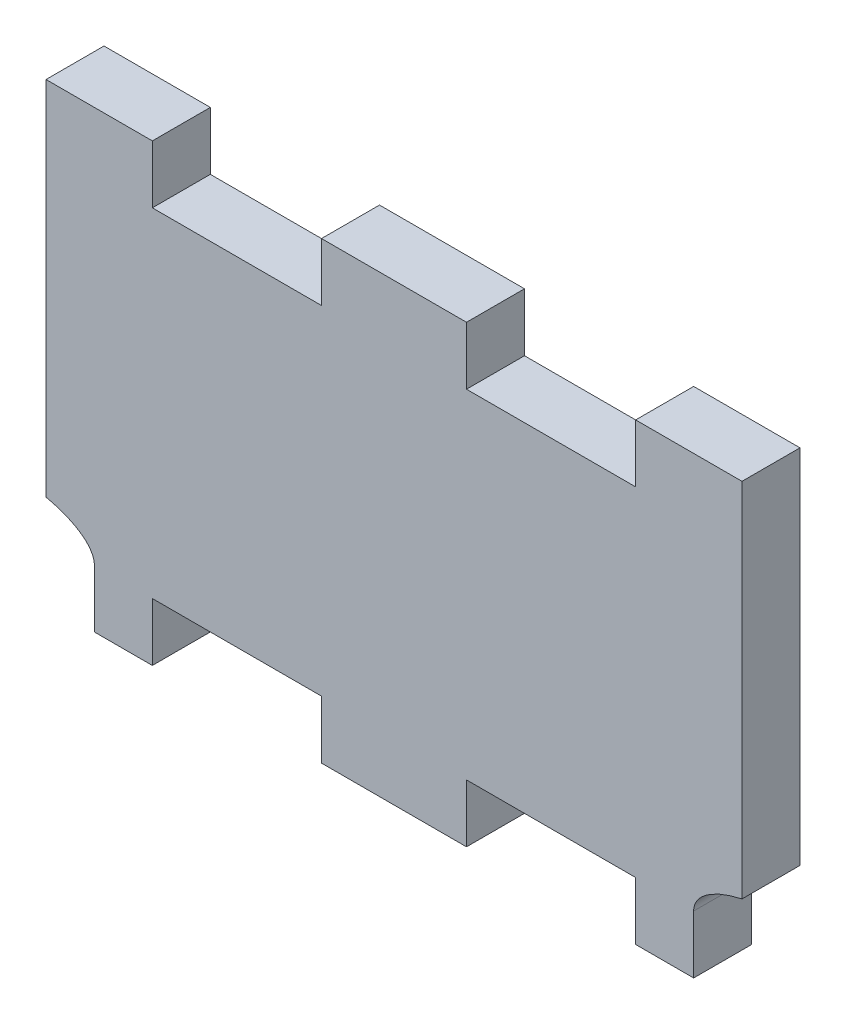
SolidWorks part; units mm, degrees
ref_plane "Front" through (0, 0, 0) normal (0, 0, 1) x (1, 0, 0)
ref_plane "Top" through (0, 0, 0) normal (0, 1, 0) x (1, 0, 0)
ref_plane "Right" through (0, 0, 0) normal (1, 0, 0) x (0, 0, -1)
sketch "Sketch2" plane through (0, 0, 0) normal (0, 0, 1) x (1, 0, 0)
  line L0 (0, 41) -> (-80, 41) construction
  line L1 (0, 0) -> (-80, 0)
  line L2 (0, 0) -> (0, 47)
  line L3 (0, 47) -> (-80, 47)
  line L4 (-80, 0) -> (-80, 47)
  line L5 (0, 6) -> (-80, 6) construction
  line L6 (-4, 0) -> (-4, 47) construction
  line L7 (-15, 0) -> (-15, 47) construction
  line L8 (-76, 0) -> (-76, 47) construction
  line L9 (-65, 0) -> (-65, 47) construction
  line L10 (-47.5, 0) -> (-47.5, 47) construction
  line L11 (-32.5, 0) -> (-32.5, 47) construction
  line L12 (-80, 41) -> (-76, 41)
  line L13 (-76, 41) -> (-76, 47)
  line L14 (-76, 47) -> (-65, 47)
  line L15 (-65, 47) -> (-65, 41)
  line L16 (-65, 41) -> (-47.5, 41)
  line L17 (-47.5, 41) -> (-47.5, 47)
  line L18 (-47.5, 47) -> (-32.5, 47)
  line L19 (-32.5, 47) -> (-32.5, 41)
  line L20 (-32.5, 41) -> (-15, 41)
  line L21 (-15, 41) -> (-15, 47)
  line L22 (-15, 47) -> (-4, 47)
  line L23 (-4, 47) -> (-4, 41)
  line L24 (-4, 41) -> (0, 41)
  line L25 (0, 6) -> (-4, 6)
  line L26 (-4, 6) -> (-4, 0)
  line L27 (-4, 0) -> (-15, 0)
  line L28 (-15, 0) -> (-15, 6)
  line L29 (-15, 6) -> (-32.5, 6)
  line L30 (-32.5, 6) -> (-32.5, 0)
  line L31 (-32.5, 0) -> (-47.5, 0)
  line L32 (-47.5, 0) -> (-47.5, 6)
  line L33 (-47.5, 6) -> (-65, 6)
  line L34 (-65, 6) -> (-65, 0)
  line L35 (-65, 0) -> (-76, 0)
  line L36 (-76, 0) -> (-76, 6)
  line L37 (-76, 6) -> (-80, 6)
  line L38 (-4, 41) -> (-4, 6)
  line L39 (-76, 6) -> (-76, 41)
  line L40 (-9, 6) -> (-9, 0)
  line L41 (-40, 0) -> (-40, 47) construction
  line L42 (-71, 0) -> (-71, 47) construction
  line L43 (-71, 6) -> (-71, 0)
  line L44 (-76, 41) -> (-76, 9.5832)
  line L45 (-4, 41) -> (-4, 9.5832)
  ellipse E0 centre (0, 6) end of major axis (-9, 6) minor radius 4
  ellipse E1 centre (-80, 6) end of major axis (-71, 6) minor radius 4
  dimension "D1" = 47
  dimension "D2" = 80
  dimension "D11" = 6
  dimension "D10" = 32.5
  dimension "D12" = 4
  dimension "D15" = 4
  dimension "D3" = 6
  dimension "D4" = 6
  dimension "D5" = 4
  dimension "D6" = 15
  dimension "D7" = 4
  dimension "D8" = 15
  dimension "D9" = 32.5
  dimension "D13" = 40
  dimension "D14" = 9
extrude "Boss-Extrude1" add sketch "Sketch2" along normal blind 6 contours L37 L36 L1 L34 L33 L32 L30 L29 L28 L26 L25 L2 L24 L23 L3 L21 L20 L19 L17 L16 L15 L13 L12 L4
